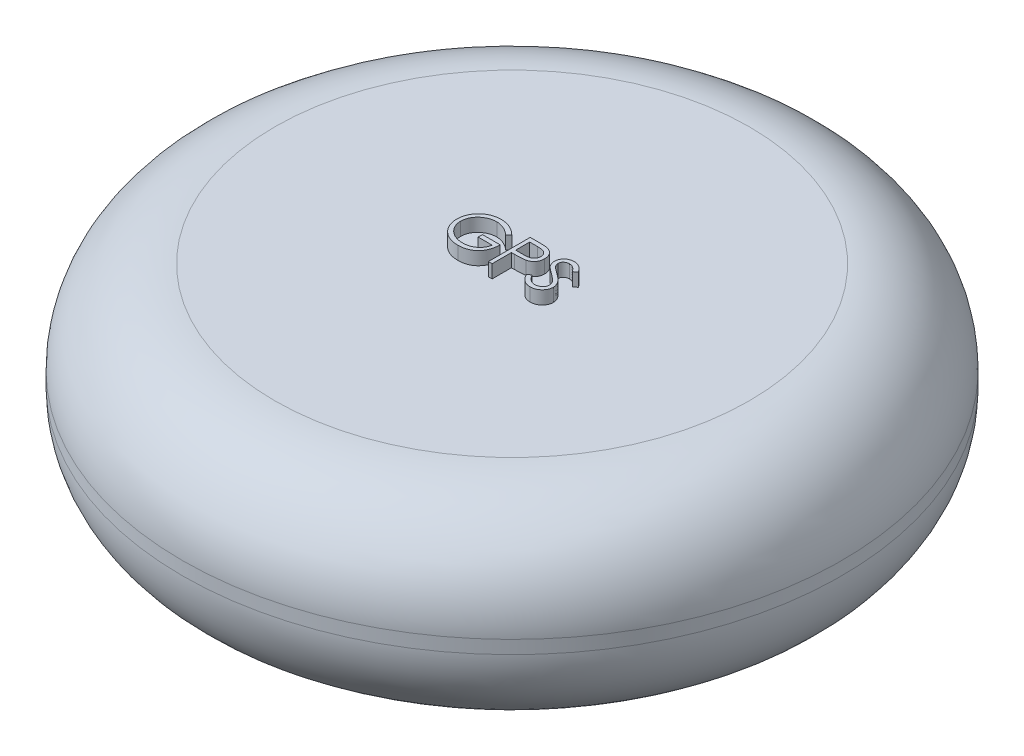
SolidWorks part; units mm, degrees
ref_plane "Front Plane" through (0, 0, 0) normal (0, 0, 1) x (1, 0, 0)
ref_plane "Top Plane" through (0, 0, 0) normal (0, 1, 0) x (1, 0, 0)
ref_plane "Right Plane" through (0, 0, 0) normal (1, 0, 0) x (0, 0, -1)
sketch "Sketch1" plane through (0, 0, 0) normal (0, 1, 0) x (1, 0, 0)
  circle A0 centre (0, 0) radius 25
extrude "Boss-Extrude1" add sketch "Sketch1" along normal blind 15
fillet "Fillet7" radius 7 2 edges at (0, 0, 25) (0, 15, 25)
sketch "Sketch2" plane through (0, 15, 0) normal (0, 1, 0) x (1, 0, 0)
  text T0 "GPS"
extrude "Boss-Extrude2" add sketch "Sketch2" along normal blind 1
